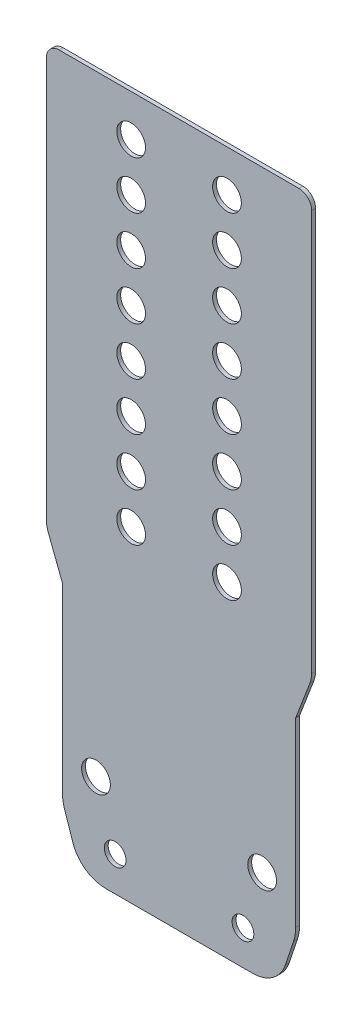
SolidWorks part; units mm, degrees
ref_plane "Front Plane" through (0, 0, 0) normal (0, 0, 1) x (1, 0, 0)
ref_plane "Top Plane" through (0, 0, 0) normal (0, 1, 0) x (1, 0, 0)
ref_plane "Right Plane" through (0, 0, 0) normal (1, 0, 0) x (0, 0, -1)
sketch "Sketch2" plane through (0, 0, 0) normal (0, 0, 1) x (1, 0, 0)
  line L0 (34.8835, 3.6866) -> (36.1641, 7.5139)
  line L1 (6.7374, 0) -> (29.7626, 0)
  line L2 (0, 9.5763) -> (0, 108)
  line L3 (2, 110) -> (34.5, 110)
  line L4 (36.5, 9.5763) -> (36.5, 108)
  line L5 (1.6165, 3.6866) -> (0.3359, 7.5139)
  arc A0 (34.8835, 3.6866) -> (29.7626, 0) centre (29.7626, 5.4) cw
  arc A1 (1.6165, 3.6866) -> (6.7374, 0) centre (6.7374, 5.4) ccw
  arc A2 (36.1641, 7.5139) -> (36.5, 9.5763) centre (30, 9.5763) ccw
  arc A3 (0.3359, 7.5139) -> (0, 9.5763) centre (6.5, 9.5763) cw
  arc A4 (34.5, 110) -> (36.5, 108) centre (34.5, 108) cw
  arc A5 (0, 108) -> (2, 110) centre (2, 108) cw
  point P11 (33.65, 0)
  point P14 (2.85, 0)
  point P17 (36.5, 8.5178)
  point P20 (0, 8.5178)
  dimension "D6" = 5.4
  dimension "D7" = 6.5
  dimension "D1" = 36.5
  dimension "D2" = 110
  dimension "D3" = 71.5
  dimension "D4" = 71.5
  dimension "D5" = 30.8
extrude "Boss-Extrude1" add sketch "Sketch2" along normal blind 0.6096
sketch "Sketch3" plane through (0, 0, 0.6096) normal (0, 0, 1) x (1, 0, 0)
  line L3 (18.25, 0) -> (18.25, 110) construction
  line L4 (6.7374, 0) -> (29.7626, 0) construction
  line L5 (34.5, 110) -> (2, 110) construction
  circle A0 centre (8.25, 5.4) radius 1.7
  circle A1 centre (5.25, 14.4) radius 2.25
  circle A3 centre (10.75, 103.5) radius 2.25
  circle A4 centre (28.25, 5.4) radius 1.7
  circle A5 centre (31.25, 14.4) radius 2.25
  circle A6 centre (25.75, 103.5) radius 2.25
  point P7 (3, 14.4)
  dimension "D1" = 3.4
  dimension "D3" = 4.5
  dimension "D7" = 4.5
  dimension "D2" = 10
  dimension "D4" = 3
  dimension "D5" = 9
  dimension "D6" = 5.4
  dimension "D8" = 6.5
  dimension "D9" = 7.5
extrude "Cut-Extrude1" cut sketch "Sketch3" against normal through all
sketch "Sketch5" plane through (0, 0, 0.6096) normal (0, 0, 1) x (1, 0, 0)
  line L0 (10.75, 103.5) -> (10.75, 0) construction
  line L1 (6.7374, 0) -> (29.7626, 0) construction
  line L2 (25.75, 103.5) -> (25.75, 0) construction
  circle A0 centre (10.75, 96) radius 2.25
  circle A1 centre (25.75, 96) radius 2.25
  dimension "D1" = 4.5
  dimension "D2" = 4.5
  dimension "D3" = 7.5
  dimension "D4" = 7.5
extrude "Cut-Extrude2" cut sketch "Sketch5" against normal through all
pattern_linear "LPattern1" count 7 spacing 7.5 along (0, -1, 0) of "Cut-Extrude2"
sketch "Sketch7" plane through (0, 0, 0.6096) normal (0, 0, 1) x (1, 0, 0)
  line L0 (36.5, 38) -> (38.7334, 43.8068)
  line L1 (36.5, 9.5763) -> (36.5, 108) construction
  line L2 (18.25, 0) -> (18.25, 110) construction
  line L3 (6.7374, 0) -> (29.7626, 0) construction
  line L4 (34.5, 110) -> (2, 110) construction
  line L5 (39, 45.2427) -> (39, 108)
  line L6 (37, 110) -> (34.5, 110)
  line L7 (36.5, 9.5763) -> (36.5, 108)
  line L9 (34.5, 38) -> (36.5, 38)
  line L10 (34.5, 110) -> (34.5, 38)
  line L11 (2, 110) -> (2, 38)
  line L12 (2, 38) -> (0, 38)
  line L13 (-0.5, 110) -> (2, 110)
  line L14 (-2.5, 45.2427) -> (-2.5, 108)
  line L15 (0, 38) -> (-2.2334, 43.8068)
  circle A0 centre (25.75, 51) radius 2.25 construction
  arc A3 (39, 108) -> (37, 110) centre (37, 108) ccw
  arc A4 (38.7334, 43.8068) -> (39, 45.2427) centre (35, 45.2427) ccw
  arc A5 (-2.2334, 43.8068) -> (-2.5, 45.2427) centre (1.5, 45.2427) cw
  arc A6 (-2.5, 108) -> (-0.5, 110) centre (-0.5, 108) cw
  point P19 (34.5, 108)
  point P20 (39, 44.5)
  point P21 (0, 0)
  point P31 (-2.5, 44.5)
  point P32 (2, 108)
  line M23 (36.5, 9.5763) -> (36.5, 108)
  arc M24 (36.5, 108) -> (34.5, 110) centre (34.5, 108) ccw
  arc M26 (2, 110) -> (0, 108) centre (2, 108) ccw
  line M27 (0, 108) -> (0, 9.5763)
  dimension "D4" = 2
  dimension "D5" = 4
  dimension "D1" = 2.5
  dimension "D2" = 6.5
  dimension "D3" = 6.5
  dimension "D6" = 16.25
extrude "Boss-Extrude2" add sketch "Sketch7" against normal up to surface (0.6096 mm away) contours A6 L14 A5 L15 L13 M27 M26 | L0 A4 L5 A3 L6 M24 M23 up to face at (28, 88.5, 0)
